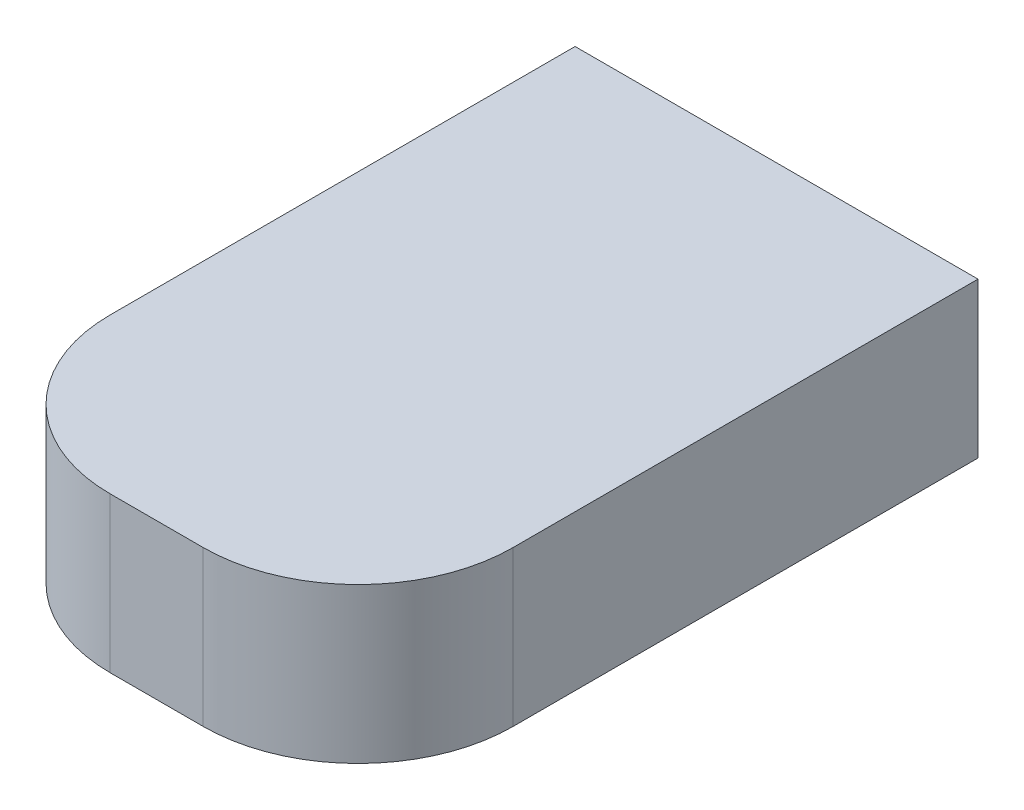
SolidWorks part; units mm, degrees
material "AISI 304"
ref_plane "Front Plane" through (0, 0, 0) normal (0, 0, 1) x (1, 0, 0)
ref_plane "Top Plane" through (0, 0, 0) normal (0, 1, 0) x (1, 0, 0)
ref_plane "Right Plane" through (0, 0, 0) normal (1, 0, 0) x (0, 0, -1)
sketch "Sketch1" plane through (0, 0, 0) normal (0, 1, 0) x (1, 0, 0)
  line L1 (-1.95, -3) -> (1.95, -3)
  line L2 (-1.95, -3) -> (-1.95, 3)
  line L3 (-1.95, 3) -> (1.95, 3)
  line L4 (1.95, -3) -> (1.95, 3)
  line L5 (-1.95, -3) -> (1.95, 3) construction
  line L6 (-1.95, 3) -> (1.95, -3) construction
  point P0 (0, 0)
  dimension "D1" = 3.9
  dimension "D2" = 6
extrude "Boss-Extrude1" add sketch "Sketch1" along normal blind 1.5
fillet "Fillet1" radius 1.5 2 edges at (1.95, 0.75, 3) (-1.95, 0.75, 3)
